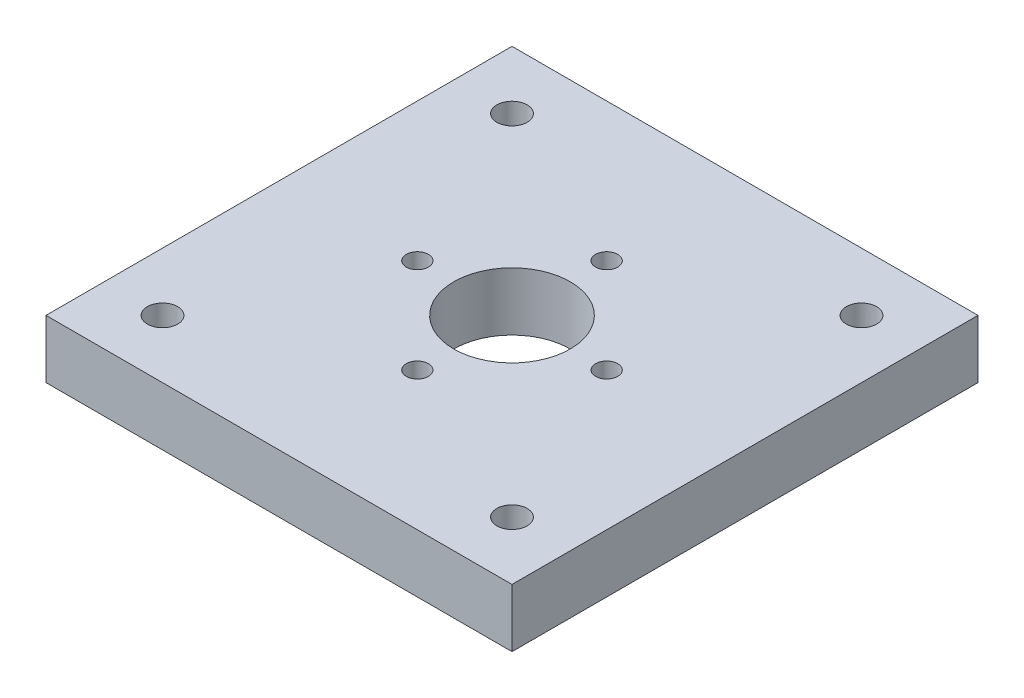
SolidWorks part; units mm, degrees
ref_plane "Front Plane" through (0, 0, 0) normal (0, 0, 1) x (1, 0, 0)
ref_plane "Top Plane" through (0, 0, 0) normal (0, 1, 0) x (1, 0, 0)
ref_plane "Right Plane" through (0, 0, 0) normal (1, 0, 0) x (0, 0, -1)
sketch "Sketch1" plane through (0, 0, 0) normal (0, 1, 0) x (1, 0, 0)
  line L0 (0, 1.5455) -> (0, -1.7677) construction
  line L1 (-2.3434, 0) -> (2.4646, 0) construction
  line L3 (-2, 2) -> (2, 2)
  line L4 (-2, 2) -> (-2, -2)
  line L5 (-2, -2) -> (2, -2)
  line L6 (2, 2) -> (2, -2)
  circle A0 centre (-1.5, 1.5) radius 0.13
  circle A1 centre (-1.5, -1.5) radius 0.13
  circle A2 centre (1.5, -1.5) radius 0.13
  circle A3 centre (1.5, 1.5) radius 0.13
  circle A4 centre (0, 0) radius 0.5
  circle A6 centre (0, 0) radius 0.8125 construction
  circle A7 centre (0, 0.8125) radius 0.095
  circle A8 centre (0.8125, 0) radius 0.095
  circle A9 centre (0, -0.8125) radius 0.095
  circle A10 centre (-0.8125, 0) radius 0.095
  point P5 (0, 0)
  point P32 (0, 0)
  dimension "D7" = 0.26
  dimension "D8" = 0.26
  dimension "D9" = 0.19
  dimension "D10" = 1
  dimension "D12" = 1.625
  dimension "D1" = 4
  dimension "D2" = 4
  dimension "D3" = 0.5
  dimension "D4" = 0.5
  dimension "D5" = 0.5
  dimension "D6" = 0.5
  dimension "D11" = 2
  dimension "D14" = 3
  dimension "D13" = 4
extrude "Boss-Extrude1" add sketch "Sketch1" along normal blind 0.5
